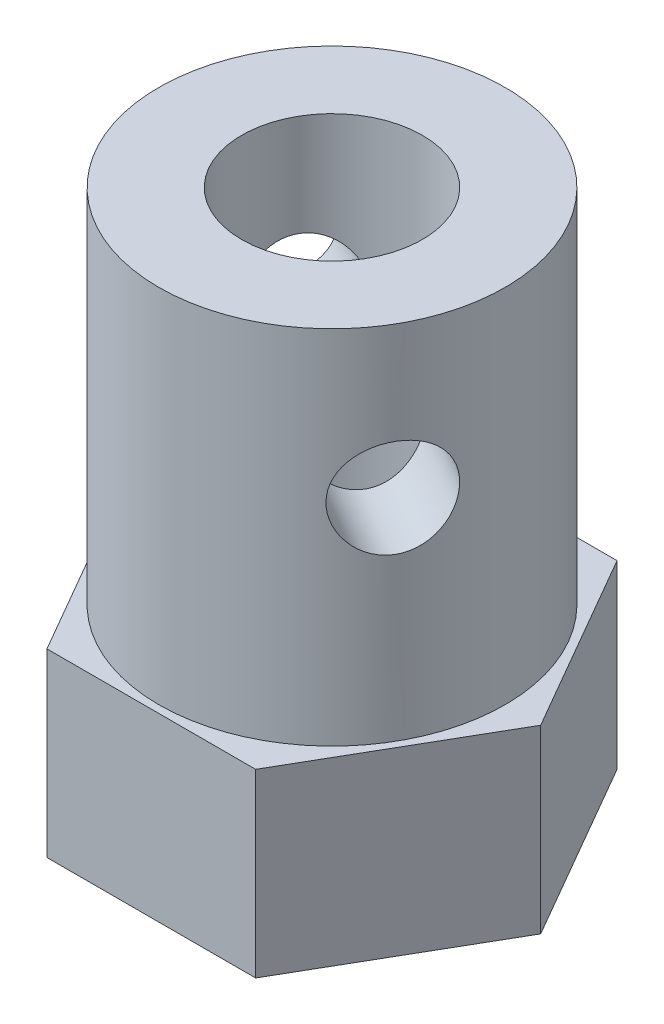
SolidWorks part; units mm, degrees
ref_plane "Спереди" through (0, 0, 0) normal (0, 0, 1) x (1, 0, 0)
ref_plane "Сверху" through (0, 0, 0) normal (0, 1, 0) x (1, 0, 0)
ref_plane "Справа" through (0, 0, 0) normal (1, 0, 0) x (0, 0, -1)
sketch "Эскиз1" plane through (0, 0, 0) normal (0, 1, 0) x (1, 0, 0)
  line L1 (6.9282, 0) -> (3.4641, 6)
  line L2 (3.4641, 6) -> (-3.4641, 6)
  line L3 (-3.4641, 6) -> (-6.9282, 0)
  line L4 (-6.9282, 0) -> (-3.4641, -6)
  line L5 (-3.4641, -6) -> (3.4641, -6)
  line L6 (3.4641, -6) -> (6.9282, 0)
  circle A0 centre (0, 0) radius 6 construction
extrude "Бобышка-Вытянуть1" add sketch "Эскиз1" along normal blind 6
sketch "Эскиз2" plane through (0, 6, 0) normal (0, 1, 0) x (1, 0, 0)
  circle A0 centre (0, 0) radius 5.75
extrude "Бобышка-Вытянуть2" add sketch "Эскиз2" along normal blind 12
sketch "Эскиз3" plane through (0, 0, 0) normal (0, -1, 0) x (1, 0, 0)
  circle A0 centre (0, 0) radius 1.625
extrude "Вырез-Вытянуть1" cut sketch "Эскиз3" against normal blind 300 contours A0
sketch "Эскиз4" plane through (0, 18, 0) normal (0, 1, 0) x (1, 0, 0)
  circle A0 centre (0, 0) radius 3
extrude "Вырез-Вытянуть2" cut sketch "Эскиз4" against normal blind 12
sketch "Эскиз5" plane through (-5.1962, 0, -3) normal (-0.866, 0, -0.5) x (-0.5, 0, 0.866)
  circle A0 centre (0, 13) radius 1.625
extrude "Вырез-Вытянуть3" cut sketch "Эскиз5" against normal blind 12
